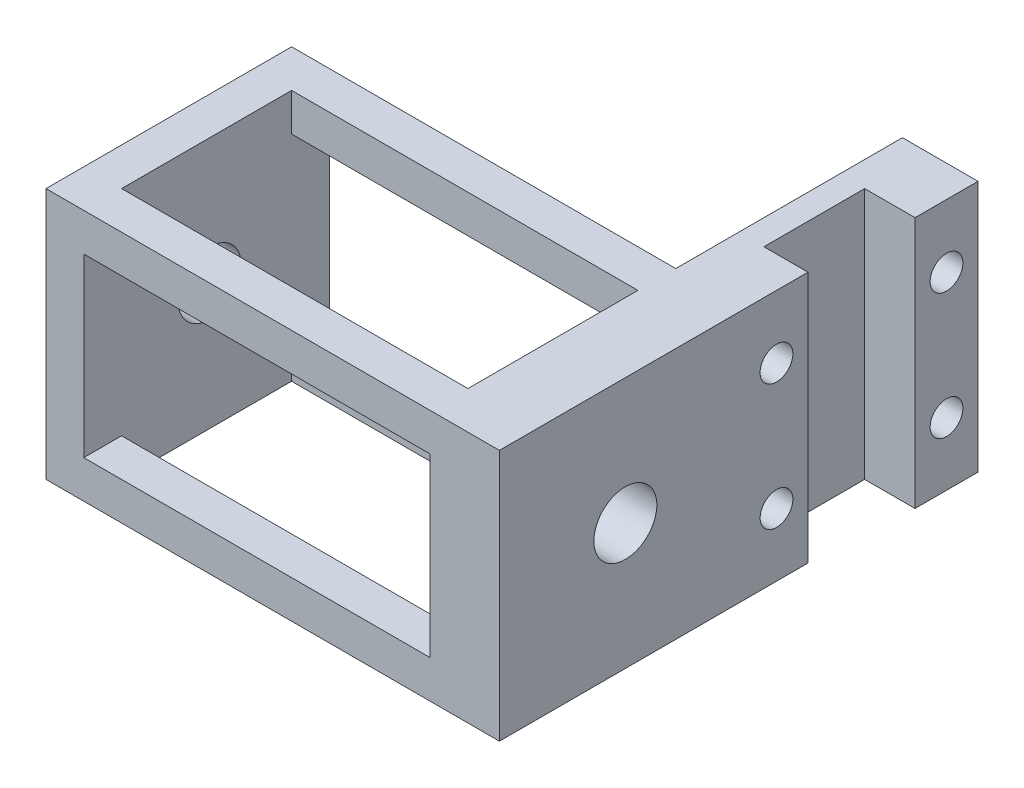
SolidWorks part; units mm, degrees
ref_plane "Front Plane" through (0, 0, 0) normal (1, 0, 0) x (0, 1, 0)
ref_plane "Top Plane" through (0, 0, 0) normal (0, 0, 1) x (0, 1, 0)
ref_plane "Right Plane" through (0, 0, 0) normal (0, 1, 0) x (-1, 0, 0)
sketch "Sketch1" plane through (0, 0, 0) normal (0, 1, 0) x (-1, 0, 0)
  line L0 (2.8934, -2.3689) -> (2.8934, 22.1311)
  line L1 (2.8934, 22.1311) -> (8.3934, 22.1311)
  line L2 (8.3934, 22.1311) -> (8.3934, -15.3689)
  line L3 (8.3934, -15.3689) -> (2.3934, -15.3689)
  line L4 (2.3934, -15.3689) -> (2.3934, -10.3689)
  line L5 (2.3934, -10.3689) -> (6.3934, -10.3689)
  line L6 (6.3934, -10.3689) -> (6.3934, -2.3689)
  line L7 (6.3934, -2.3689) -> (2.8934, -2.3689)
  dimension "D1" = 5
  dimension "D2" = 24.5
  dimension "D3" = 3.5
  dimension "D4" = 4
  dimension "D5" = 8
  dimension "D6" = 2
extrude "Boss-Extrude1" add sketch "Sketch1" along normal blind 20
sketch "Sketch4" plane through (0, 20, 0) normal (0, 1, 0) x (-1, 0, 0)
  line L1 (8.3934, 22.1311) -> (38.8934, 22.1311)
  line L2 (8.3934, 22.1311) -> (8.3934, 2.6311)
  line L3 (8.3934, 2.6311) -> (38.8934, 2.6311)
  line L4 (38.8934, 22.1311) -> (38.8934, 2.6311)
  dimension "D1" = 30.5
  dimension "D2" = 19.5
extrude "Boss-Extrude2" add sketch "Sketch4" against normal blind 20
sketch "Sketch6" plane through (0, 20, 0) normal (0, 1, 0) x (-1, 0, 0)
  line L0 (8.3934, -15.3689) -> (8.3934, 2.6311) construction
  line L1 (8.3934, 19.1311) -> (35.8934, 19.1311)
  line L2 (8.3934, 19.1311) -> (8.3934, 5.6311)
  line L3 (8.3934, 5.6311) -> (35.8934, 5.6311)
  line L4 (35.8934, 19.1311) -> (35.8934, 5.6311)
  line L5 (38.8934, 22.1311) -> (2.8934, 22.1311) construction
  line L6 (8.3934, 2.6311) -> (38.8934, 2.6311) construction
  line L7 (38.8934, 2.6311) -> (38.8934, 22.1311) construction
  dimension "D1" = 3
  dimension "D2" = 3
  dimension "D3" = 3
extrude "Cut-Extrude1" cut sketch "Sketch6" against normal up to next
sketch "Sketch7" plane through (0, 0, 22.1311) normal (0, 0, 1) x (1, 0, 0)
  line L0 (-2.8934, 20) -> (-2.8934, 0) construction
  line L1 (-35.8934, 17) -> (-8.3934, 17)
  line L2 (-35.8934, 17) -> (-35.8934, 3)
  line L3 (-35.8934, 3) -> (-8.3934, 3)
  line L4 (-8.3934, 17) -> (-8.3934, 3)
  line L5 (-38.8934, 0) -> (-38.8934, 20) construction
  line L6 (-38.8934, 20) -> (-2.8934, 20) construction
  line L7 (-38.8934, 0) -> (-2.8934, 0) construction
  dimension "D1" = 5.5
  dimension "D2" = 3
  dimension "D3" = 3
  dimension "D4" = 3
extrude "Cut-Extrude2" cut sketch "Sketch7" against normal through all
sketch "Sketch9" plane through (-38.8934, 0, 0) normal (-1, 0, 0) x (0, -1, 0)
  line L0 (-20, 12.1311) -> (0, 12.1311) construction
  line L3 (0, 2.6311) -> (-20, 2.6311) construction
  circle A0 centre (-10, 12.1311) radius 2.5
  dimension "D1" = 5
  dimension "D2" = 9.5
extrude "Cut-Extrude3" cut sketch "Sketch9" against normal through all
sketch "Sketch10" plane through (-2.3934, 0, 0) normal (1, 0, 0) x (0, 1, 0)
  line L0 (0, -12.8689) -> (20, -12.8689) construction
  line L1 (0, -10.3689) -> (0, -15.3689) construction
  line L2 (20, -10.3689) -> (20, -15.3689) construction
  line L3 (10, -10.3689) -> (10, -15.3689) construction
  line L4 (20, -10.3689) -> (0, -10.3689) construction
  line L5 (20, -15.3689) -> (0, -15.3689) construction
  circle A0 centre (5, -12.8689) radius 1.3
  circle A1 centre (15, -12.8689) radius 1.3
  dimension "D1" = 2.6
  dimension "D2" = 5
extrude "Cut-Extrude4" cut sketch "Sketch10" against normal up to next
sketch "Sketch11" plane through (-2.8934, 0, 0) normal (1, 0, 0) x (0, 1, 0)
  line L0 (0, 0.1311) -> (20, 0.1311) construction
  line L1 (0, 22.1311) -> (0, -2.3689) construction
  line L2 (20, 22.1311) -> (20, -2.3689) construction
  line L3 (20, -2.3689) -> (0, -2.3689) construction
  line L4 (10, 22.1311) -> (10, -2.3689) construction
  line L5 (20, 22.1311) -> (0, 22.1311) construction
  circle A0 centre (5, 0.1311) radius 1.3
  circle A1 centre (15, 0.1311) radius 1.3
  dimension "D3" = 2.6
  dimension "D1" = 2.5
  dimension "D2" = 5
extrude "Cut-Extrude5" cut sketch "Sketch11" against normal up to next
